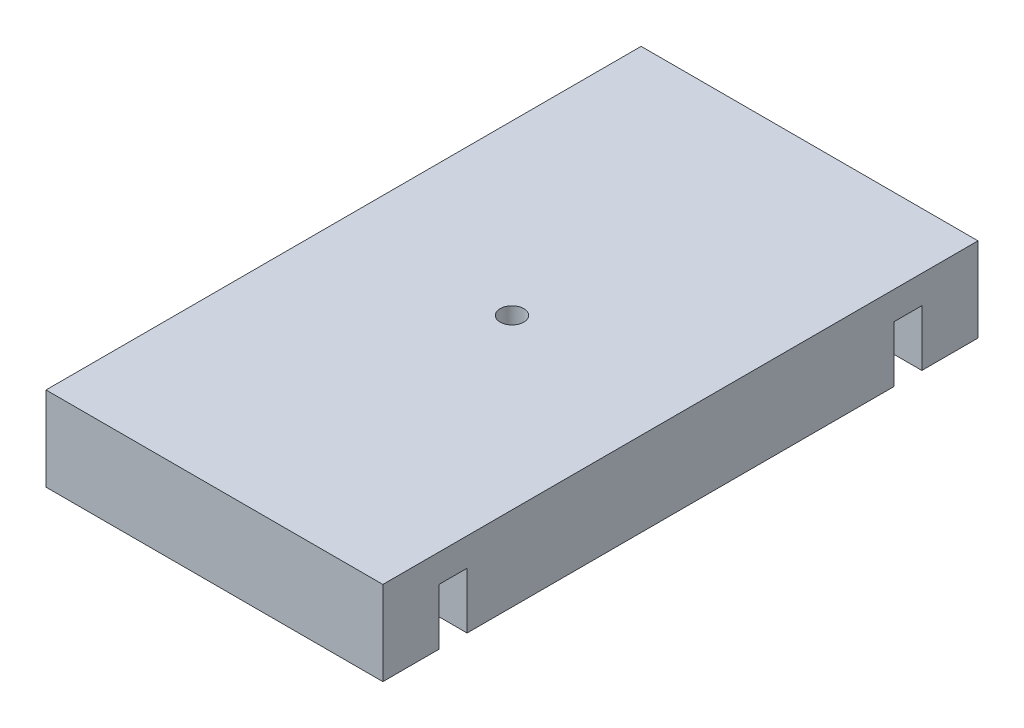
SolidWorks part; units mm, degrees
ref_plane "前视基准面" through (0, 0, 0) normal (0, 0, 1) x (1, 0, 0)
ref_plane "a" through (0, 0, 0) normal (0, 1, 0) x (1, 0, 0)
ref_plane "右视基准面" through (0, 0, 0) normal (1, 0, 0) x (0, 0, -1)
other "Configuration Table"
sketch "草图1" plane through (0, 0, 0) normal (0, 1, 0) x (1, 0, 0)
  line L1 (-30, 53) -> (30, 53)
  line L2 (-30, 53) -> (-30, -53)
  line L3 (-30, -53) -> (30, -53)
  line L4 (30, 53) -> (30, -53)
  line L5 (-30, 53) -> (30, -53) construction
  line L6 (-30, -53) -> (30, 53) construction
  point P0 (0, 0)
  dimension "D1" = 60
  dimension "D2" = 106
extrude "凸台-拉伸1" add sketch "草图1" along normal blind 15
sketch "草图2" plane through (0, 0, 0) normal (0, -1, 0) x (1, 0, 0)
  line L0 (-32.9578, 43) -> (38.6402, 43)
  line L1 (38.6402, 43) -> (38.6402, 38)
  line L2 (38.6402, 38) -> (-35.799, 38)
  line L3 (-35.799, 38) -> (-32.9578, 43)
  line L4 (-46.1693, 0) -> (55.2612, 0) construction
  line L6 (38.6402, -38) -> (-35.799, -38)
  line L7 (38.6402, -43) -> (38.6402, -38)
  line L8 (-32.9578, -43) -> (38.6402, -43)
  line L9 (-35.799, -38) -> (-32.9578, -43)
  dimension "D2" = 5
  dimension "D3" = 38
extrude "切除-拉伸1" cut sketch "草图2" against normal blind 10
sketch "草图3" plane through (0, 15, 0) normal (0, 1, 0) x (1, 0, 0)
  circle A0 centre (0, 0) radius 2.1
  dimension "D1" = 4.2
extrude "切除-拉伸2" cut sketch "草图3" against normal through all both and the other way through all
